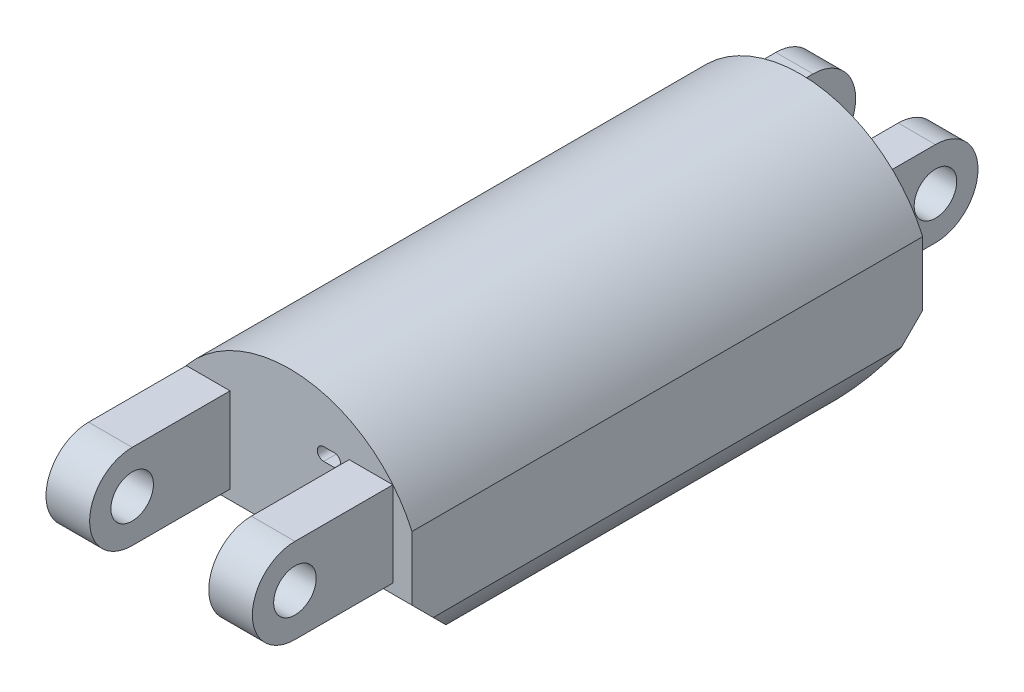
SolidWorks part; units mm, degrees
material "PET"
ref_plane "Front Plane" through (0, 0, 0) normal (0, 0, 1) x (1, 0, 0)
ref_plane "Top Plane" through (0, 0, 0) normal (0, 1, 0) x (1, 0, 0)
ref_plane "Right Plane" through (0, 0, 0) normal (1, 0, 0) x (0, 0, -1)
sketch "Sketch1" plane through (0, 0, 0) normal (0, 0, 1) x (1, 0, 0)
  line L0 (0, 0) -> (0, 5.08)
  line L3 (14.605, 5.08) -> (14.605, 0)
  arc A2 (0, 5.08) -> (14.605, 5.08) centre (7.3025, 1.8627) cw
  arc A3 (0, 0) -> (14.605, 0) centre (7.3025, 3.2173) ccw
  point P7 (7.3025, -4.7625)
  point P8 (7.3025, 9.8425)
extrude "Boss-Extrude1" add sketch "Sketch1" along normal mid plane 30.48 contours A2 L3 A3 L0
sketch "Sketch2" plane through (0, 0, 0) normal (1, 0, 0) x (0, 0, -1)
  line L4 (15.875, 2.54) -> (-49984.125, 2.54) construction
  line L5 (15.24, 5.08) -> (15.24, 0) construction
  line L6 (-15.24, 5.08) -> (-15.24, 0) construction
  line L10 (0, -1000) -> (0, 49000) construction
  line L18 (-15.24, 1.27) -> (-15.24, -4.7625)
  line L23 (15.24, -4.7625) -> (9.2075, -4.7625)
  line L24 (15.24, 1.27) -> (15.24, -4.7625)
  line L32 (-15.24, -4.7625) -> (-9.2075, -4.7625)
  line L33 (-15.24, -4.7625) -> (15.24, -4.7625) construction
  line L34 (-9.2075, -4.7625) -> (-15.24, 1.27)
  line L35 (9.2075, -4.7625) -> (15.24, 1.27)
  line L36 (-15.24, -4.7625) -> (15.24, -4.7625) construction
  point P0 (-15.0884, 2.54)
  point P11 (15.24, 2.54)
  point P14 (-15.24, 2.54)
  dimension "D2" = 1.27
  dimension "D4" = 45
extrude "Cut-Extrude1" cut sketch "Sketch2" along normal through all
sketch "Sketch3" plane through (0, 0, 15.24) normal (0, 0, 1) x (1, 0, 0)
  line L0 (-4.2391, 2.54) -> (20.243, 2.54) construction
  line L2 (7.3025, 10.7465) -> (7.3025, -6.8749) construction
  line L3 (14.605, 1.27) -> (0, 1.27) construction
  arc A3 (0, 0) -> (14.605, 0) centre (7.3025, 3.2173) ccw construction
  arc A7 (13.1998, 1.27) -> (1.4052, 1.27) centre (7.3025, 2.54) cw
  arc A8 (4.2394, -2.657) -> (10.3656, -2.657) centre (7.3025, -3.4925) cw
  arc A9 (14.605, 5.08) -> (0, 5.08) centre (7.3025, 1.8627) ccw construction
  point P13 (7.3025, 9.8425)
  dimension "D1" = 2.54
  dimension "D2" = 3.175
  dimension "D3" = 1.27
extrude "Cut-Extrude2" cut sketch "Sketch3" against normal through all contours A8 A7
ref_plane "Plane1" through (9.525, 0, 0) normal (1, 0, 0) x (0, 0, -1)
sketch "Sketch4" plane through (9.525, 0, 0) normal (1, 0, 0) x (0, 0, -1)
  line L0 (-15.24, 6.9215) -> (-18.542, 6.9215)
  line L1 (-15.24, 6.9215) -> (-15.24, 1.8415)
  line L2 (-15.24, 1.8415) -> (-18.542, 1.8415)
  line L3 (-15.24, 5.08) -> (-15.24, 1.27) construction
  line L4 (-13.97, 0) -> (13.97, 0) construction
  arc A0 (-18.542, 6.9215) -> (-18.542, 1.8415) centre (-18.542, 4.3815) ccw
  circle A1 centre (-18.542, 4.3815) radius 1.27
  dimension "D2" = 2.54
  dimension "D1" = 5.08
  dimension "D3" = 3.302
  dimension "D4" = 1.8415
extrude "Boss-Extrude2" add sketch "Sketch4" along normal mid plane 1.27
sketch "Sketch5" plane through (8.89, 0, 0) normal (-1, 0, 0) x (0, 0, 1)
  line L3 (15.24, 6.9215) -> (15.24, 1.8415)
  line L4 (15.24, 1.8415) -> (18.542, 1.8415)
  line L5 (18.542, 6.9215) -> (15.24, 6.9215)
  line L6 (15.24, 6.9215) -> (15.24, 1.8415)
  line L7 (15.24, 1.8415) -> (18.542, 1.8415)
  line L8 (18.542, 6.9215) -> (15.24, 6.9215)
  circle A0 centre (18.542, 4.3815) radius 1.27 construction
  arc A1 (18.542, 1.8415) -> (18.542, 6.9215) centre (18.542, 4.3815) ccw
  arc A2 (18.542, 1.8415) -> (18.542, 6.9215) centre (18.542, 4.3815) ccw
  circle A3 centre (18.542, 4.3815) radius 1.27
  dimension "D1" = 0
extrude "Boss-Extrude3" add sketch "Sketch5" along normal blind 1.27
ref_plane "Plane2" through (7.3025, 0, 0) normal (1, 0, 0) x (0, 0, -1)
mirror "Mirror1" about plane through (7.3025, 0, 0) normal (1, 0, 0) of "Boss-Extrude3", "Boss-Extrude2"
mirror "Mirror2" about plane through (0, 0, 0) normal (0, 0, 1) of "Mirror1", "Boss-Extrude3", "Boss-Extrude2"
sketch "Sketch21" plane through (7.3025, 0, 0) normal (1, 0, 0) x (0, 0, -1)
  line L3 (-15.24, 1.8415) -> (-15.24, 6.9215)
  line L4 (-15.24, 6.9215) -> (-18.542, 6.9215)
  line L5 (-18.542, 1.8415) -> (-15.24, 1.8415)
  line L6 (-15.24, 1.8415) -> (-15.24, 6.9215)
  line L7 (-15.24, 6.9215) -> (-18.542, 6.9215)
  line L8 (-18.542, 1.8415) -> (-15.24, 1.8415)
  circle A0 centre (-18.542, 4.3815) radius 1.27 construction
  arc A1 (-18.542, 6.9215) -> (-18.542, 1.8415) centre (-18.542, 4.3815) ccw
  arc A2 (-18.542, 6.9215) -> (-18.542, 1.8415) centre (-18.542, 4.3815) ccw
  circle A3 centre (-18.542, 4.3815) radius 1.27
  dimension "D1" = 0
extrude "Cut-Extrude9" cut sketch "Sketch21" against normal blind 1.905 and the other way blind 1.905
sketch "Sketch22" plane through (10.16, 0, 0) normal (1, 0, 0) x (0, 0, -1)
  line L3 (-15.24, 1.8415) -> (-15.24, 6.9215)
  line L4 (-15.24, 6.9215) -> (-18.542, 6.9215)
  line L5 (-18.542, 1.8415) -> (-15.24, 1.8415)
  line L6 (-15.24, 1.8415) -> (-15.24, 6.9215)
  line L7 (-15.24, 6.9215) -> (-18.542, 6.9215)
  line L8 (-18.542, 1.8415) -> (-15.24, 1.8415)
  circle A0 centre (-18.542, 4.3815) radius 1.27 construction
  arc A1 (-18.542, 6.9215) -> (-18.542, 1.8415) centre (-18.542, 4.3815) ccw
  arc A2 (-18.542, 6.9215) -> (-18.542, 1.8415) centre (-18.542, 4.3815) ccw
  circle A3 centre (-18.542, 4.3815) radius 1.27
  dimension "D1" = 0
extrude "Boss-Extrude12" add sketch "Sketch22" along normal blind 1.27
mirror "Mirror7" about plane through (7.3025, 0, 0) normal (1, 0, 0) of "Boss-Extrude12"
mirror "Mirror8" about plane through (0, 0, 0) normal (0, 0, 1) of "Mirror7", "Cut-Extrude9", "Boss-Extrude12"
sketch "Sketch23" plane through (7.3025, 0, 0) normal (1, 0, 0) x (0, 0, -1)
  line L5 (15.24, 1.8415) -> (18.542, 1.8415)
  line L6 (15.24, 6.9215) -> (15.24, 1.8415)
  line L8 (18.542, 6.9215) -> (15.24, 6.9215)
  line L9 (15.24, 1.8415) -> (18.542, 1.8415)
  line L10 (15.24, 6.9215) -> (15.24, 1.8415)
  line L12 (18.542, 6.9215) -> (15.24, 6.9215)
  circle A0 centre (18.542, 4.3815) radius 1.27 construction
  circle A1 centre (18.542, 4.3815) radius 1.27
  arc A3 (18.542, 1.8415) -> (18.542, 6.9215) centre (18.542, 4.3815) ccw
  arc A4 (18.542, 1.8415) -> (18.542, 6.9215) centre (18.542, 4.3815) ccw
  dimension "D1" = 0
extrude "Cut-Extrude10" cut sketch "Sketch23" against normal blind 2.54 and the other way blind 2.54
sketch "Sketch24" plane through (3.175, 0, 0) normal (-1, 0, 0) x (0, 0, 1)
  line L3 (-18.542, 1.8415) -> (-15.24, 1.8415)
  line L4 (-15.24, 1.8415) -> (-15.24, 6.9215)
  line L5 (-15.24, 6.9215) -> (-18.542, 6.9215)
  line L6 (-18.542, 1.8415) -> (-15.24, 1.8415)
  line L7 (-15.24, 1.8415) -> (-15.24, 6.9215)
  line L8 (-15.24, 6.9215) -> (-18.542, 6.9215)
  circle A0 centre (-18.542, 4.3815) radius 1.27 construction
  arc A1 (-18.542, 6.9215) -> (-18.542, 1.8415) centre (-18.542, 4.3815) ccw
  arc A2 (-18.542, 6.9215) -> (-18.542, 1.8415) centre (-18.542, 4.3815) ccw
  circle A3 centre (-18.542, 4.3815) radius 1.27
  dimension "D1" = 0
extrude "Boss-Extrude13" add sketch "Sketch24" along normal blind 0.635
mirror "Mirror9" about plane through (7.3025, 0, 0) normal (1, 0, 0) of "Boss-Extrude13"
sketch "Sketch25" plane through (11.43, 0, 0) normal (1, 0, 0) x (0, 0, -1)
  line L0 (-18.542, 1.8415) -> (-15.24, 1.8415) construction
  line L1 (-15.24, 6.9215) -> (-21.082, 6.9215)
  line L2 (-15.24, 6.9215) -> (-15.24, 1.8415)
  line L3 (-15.24, 1.8415) -> (-21.082, 1.8415)
  arc A0 (-18.542, 6.9215) -> (-18.542, 1.8415) centre (-18.542, 4.3815) ccw construction
  arc A1 (-21.082, 6.9215) -> (-21.082, 1.8415) centre (-21.082, 4.3815) ccw
  point P8 (-21.082, 4.3815)
  point P12 (-23.622, 4.3815)
  dimension "D1" = 2.54
extrude "Boss-Extrude14" add sketch "Sketch25" against normal up to surface (2.2225 mm away) up to face at (9.2075, 4.3815, 17.526)
sketch "Sketch26" plane through (3.175, 0, 0) normal (-1, 0, 0) x (0, 0, 1)
  line L1 (15.24, 6.9215) -> (21.082, 6.9215)
  line L2 (15.24, 6.9215) -> (15.24, 1.8415)
  line L3 (15.24, 1.8415) -> (21.082, 1.8415)
  arc A0 (21.082, 6.9215) -> (21.082, 1.8415) centre (21.082, 4.3815) cw
extrude "Boss-Extrude15" add sketch "Sketch26" against normal up to surface (2.2225 mm away) up to face at (5.3975, 4.3815, 17.272)
sketch "Sketch27" plane through (11.43, 0, 0) normal (1, 0, 0) x (0, 0, -1)
  line L3 (-21.082, 1.8415) -> (-15.24, 1.8415)
  line L4 (-15.24, 1.8415) -> (-15.24, 6.9215)
  line L5 (-15.24, 6.9215) -> (-21.082, 6.9215)
  line L6 (-21.082, 1.8415) -> (-15.24, 1.8415) construction
  line L7 (-15.24, 1.8415) -> (-15.24, 6.9215) construction
  line L8 (-15.24, 6.9215) -> (-21.082, 6.9215) construction
  circle A0 centre (-21.082, 4.3815) radius 1.27
  arc A2 (-21.082, 6.9215) -> (-21.082, 1.8415) centre (-21.082, 4.3815) ccw
  arc A3 (-21.082, 6.9215) -> (-21.082, 1.8415) centre (-21.082, 4.3815) ccw construction
  dimension "D2" = 2.54
  dimension "D1" = 0
extrude "Cut-Extrude11" cut sketch "Sketch27" against normal up to surface (8.255 mm away)
ref_plane "Plane3" through (7.3025, 0, 0) normal (1, 0, 0) x (0, 0, -1)
sketch "Sketch28" plane through (0, 0, -15.24) normal (0, 0, -1) x (-1, 0, 0)
  line L0 (-14.605, 1.27) -> (0, 1.27) construction
  line L7 (-5.7785, 5.5626) -> (-5.1435, 5.5626) construction
  line L9 (-5.7785, 5.9436) -> (-5.1435, 5.9436)
  line L10 (-9.9695, 0.254) -> (-4.6355, 0.254) construction
  line L11 (-9.9695, 0.254) -> (-9.9695, 5.9436) construction
  line L12 (-9.9695, 5.9436) -> (-4.6355, 5.9436) construction
  line L13 (-4.6355, 0.254) -> (-4.6355, 5.9436) construction
  line L14 (-9.9695, 0.254) -> (-4.6355, 5.9436) construction
  line L15 (-9.9695, 5.9436) -> (-4.6355, 0.254) construction
  line L16 (-5.7785, 5.1816) -> (-5.1435, 5.1816)
  line L17 (-4.7625, 6.9215) -> (-4.7625, 1.8415) construction
  arc A0 (-5.7785, 5.9436) -> (-5.7785, 5.1816) centre (-5.7785, 5.5626) ccw
  arc A1 (-5.1435, 5.1816) -> (-5.1435, 5.9436) centre (-5.1435, 5.5626) ccw
  arc A2 (-10.3656, -2.657) -> (-4.2394, -2.657) centre (-7.3025, 2.54) ccw construction
  point P0 (-7.3025, 3.0988)
  point P11 (-5.461, 5.5626)
  point P20 (-7.3025, 1.27)
  dimension "D1" = 5.6896
  dimension "D2" = 5.334
  dimension "D3" = 0.635
  dimension "D4" = 0.762
  dimension "D5" = 2.286
extrude "Cut-Extrude12" cut sketch "Sketch28" against normal blind 16.51
ref_plane "Plane4" through (7.3025, 0, 0) normal (-1, 0, 0) x (0, 0, 1)
sketch "Sketch29" plane through (7.3025, 0, 0) normal (-1, 0, 0) x (0, 0, 1)
  line L3 (15.24, 1.8415) -> (21.082, 1.8415)
  line L4 (21.082, 6.9215) -> (15.24, 6.9215)
  line L5 (15.24, 6.9215) -> (15.24, 1.8415)
  line L6 (15.24, 1.8415) -> (21.082, 1.8415)
  line L7 (21.082, 6.9215) -> (15.24, 6.9215)
  line L8 (15.24, 6.9215) -> (15.24, 1.8415)
  circle A0 centre (21.082, 4.3815) radius 1.27 construction
  arc A1 (21.082, 1.8415) -> (21.082, 6.9215) centre (21.082, 4.3815) ccw
  circle A3 centre (21.082, 4.3815) radius 1.27
  arc A6 (21.082, 1.8415) -> (21.082, 6.9215) centre (21.082, 4.3815) ccw
  dimension "D1" = 0
extrude "Cut-Extrude13" cut sketch "Sketch29" against normal mid plane 7.112
sketch "Sketch30" plane through (3.175, 0, 0) normal (-1, 0, 0) x (0, 0, 1)
  line L3 (15.24, 1.8415) -> (21.082, 1.8415)
  line L4 (21.082, 6.9215) -> (15.24, 6.9215)
  line L5 (15.24, 6.9215) -> (15.24, 1.8415)
  line L6 (15.24, 1.8415) -> (21.082, 1.8415)
  line L7 (21.082, 6.9215) -> (15.24, 6.9215)
  line L8 (15.24, 6.9215) -> (15.24, 1.8415)
  circle A0 centre (21.082, 4.3815) radius 1.27 construction
  arc A1 (21.082, 1.8415) -> (21.082, 6.9215) centre (21.082, 4.3815) ccw
  circle A3 centre (21.082, 4.3815) radius 1.27
  arc A6 (21.082, 1.8415) -> (21.082, 6.9215) centre (21.082, 4.3815) ccw
  dimension "D1" = 0
extrude "Boss-Extrude16" add sketch "Sketch30" along normal blind 2.032
sketch "Sketch31" plane through (11.43, 0, 0) normal (1, 0, 0) x (0, 0, -1)
  line L3 (-21.082, 1.8415) -> (-15.24, 1.8415)
  line L4 (-15.24, 1.8415) -> (-15.24, 6.9215)
  line L5 (-15.24, 6.9215) -> (-21.082, 6.9215)
  line L6 (-21.082, 1.8415) -> (-15.24, 1.8415)
  line L7 (-15.24, 1.8415) -> (-15.24, 6.9215)
  line L8 (-15.24, 6.9215) -> (-21.082, 6.9215)
  circle A0 centre (-21.082, 4.3815) radius 1.27 construction
  arc A1 (-21.082, 6.9215) -> (-21.082, 1.8415) centre (-21.082, 4.3815) ccw
  circle A3 centre (-21.082, 4.3815) radius 1.27
  arc A6 (-21.082, 6.9215) -> (-21.082, 1.8415) centre (-21.082, 4.3815) ccw
  dimension "D1" = 0
extrude "Boss-Extrude17" add sketch "Sketch31" along normal blind 2.032
sketch "Sketch32" plane through (0, 0, 15.24) normal (0, 0, 1) x (1, 0, 0)
  line L1 (4.6355, 1.143) -> (9.9695, 1.143) construction
  line L2 (4.6355, 1.143) -> (4.6355, 6.8326) construction
  line L3 (4.6355, 6.8326) -> (9.9695, 6.8326) construction
  line L4 (9.9695, 1.143) -> (9.9695, 6.8326) construction
  line L5 (4.6355, 1.143) -> (9.9695, 6.8326) construction
  line L6 (4.6355, 6.8326) -> (9.9695, 1.143) construction
  line L7 (14.605, 1.27) -> (0, 1.27) construction
  line L8 (9.3345, 6.4516) -> (9.9695, 6.4516) construction
  line L9 (9.3345, 6.8326) -> (9.9695, 6.8326)
  line L10 (9.3345, 6.0706) -> (9.9695, 6.0706)
  arc A0 (9.3345, 6.8326) -> (9.3345, 6.0706) centre (9.3345, 6.4516) ccw
  arc A1 (9.9695, 6.0706) -> (9.9695, 6.8326) centre (9.9695, 6.4516) ccw
  point P0 (7.3025, 3.9878)
  point P7 (9.652, 6.4516)
  point P10 (7.3025, 1.27)
  dimension "D1" = 5.6896
  dimension "D2" = 5.334
  dimension "D3" = 0.762
  dimension "D4" = 0.635
  dimension "D5" = 0.127
extrude "Cut-Extrude14" cut sketch "Sketch32" against normal blind 13.97
sketch "Sketch33" plane through (0, 0, 0) normal (-1, 0, 0) x (0, 0, 1)
  text T0 "Pinky 3\r\n\r\n"
extrude "Cut-Extrude15" cut sketch "Sketch33" against normal blind 1
equation "\"D1@Sketch1\"=0.575"
equation "\"D2@Sketch1\"=0.575"
equation "\"D1@Boss-Extrude1\"=2.00*.6"
